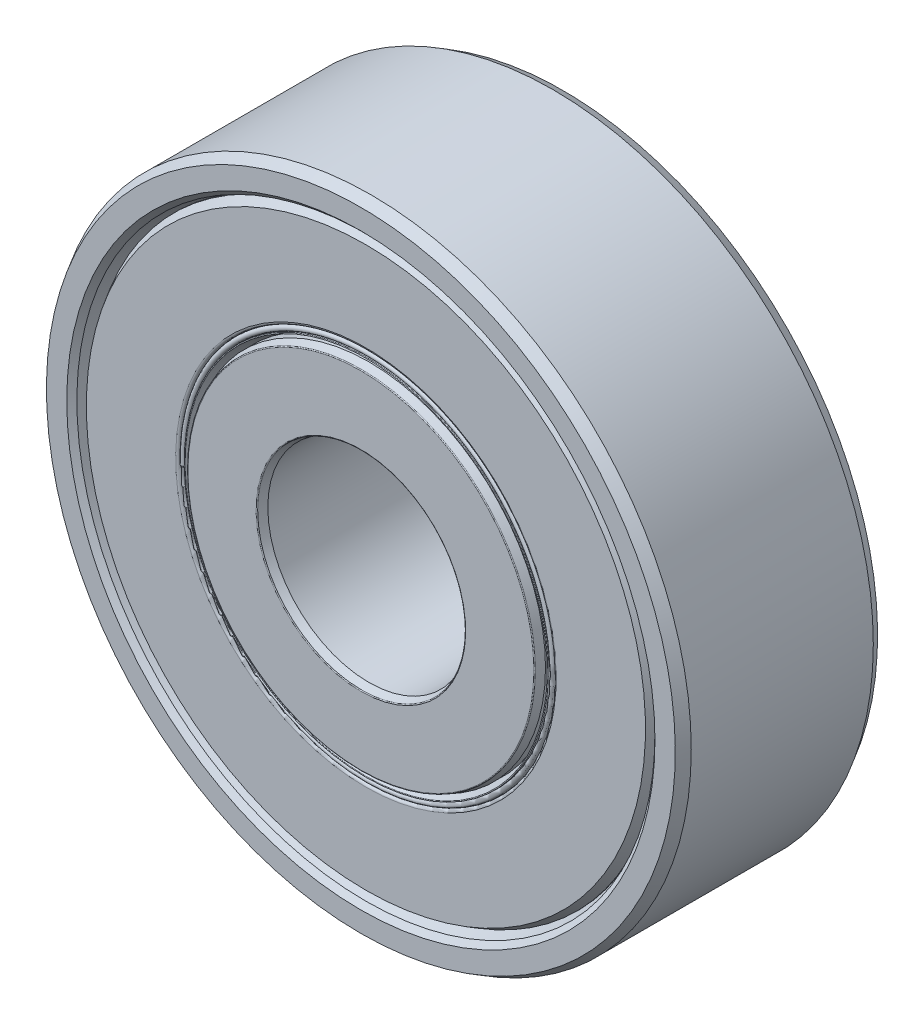
SolidWorks part; units mm, degrees
ref_plane "Front Plane" through (0, 0, 0) normal (0, 0, 1) x (1, 0, 0)
ref_plane "Top Plane" through (0, 0, 0) normal (0, 1, 0) x (1, 0, 0)
ref_plane "Right Plane" through (0, 0, 0) normal (1, 0, 0) x (0, 0, -1)
sketch "Sketch1" plane through (0, 0, 0) normal (0, 0, 1) x (1, 0, 0)
  line L0 (-9.5, 0) -> (9.5, 0) construction
  line L1 (-3, 0) -> (3, 0) construction
  circle A0 centre (0, 0) radius 3 construction
  circle A1 centre (0, 0) radius 9.5 construction
  point P3 (0, 0)
  point P6 (0, 0)
  point P7 (0, -3)
  point P11 (0, -9.5)
  point P12 (0, 3)
  point P13 (0, 9.5)
  dimension "OD" = 19
  dimension "ID" = 6
sketch "Sketch2" plane through (0, 0, 0) normal (1, 0, 0) x (0, 0, -1)
  line L0 (-3, 9.5) -> (3, 9.5) construction
  line L1 (0, 9.5) -> (0, -9.5) construction
  line L2 (2.7, 9.5) -> (-2.7, 9.5)
  line L3 (-2.7, 9.5) -> (-3, 9.3268)
  line L4 (-3, 9.3268) -> (-3, 8.7235)
  line L5 (-2.5245, 8.455) -> (-1.398, 8.455)
  line L6 (2.5245, 8.455) -> (1.398, 8.455)
  line L7 (3, 9.3268) -> (3, 8.7235)
  line L8 (2.7, 9.5) -> (3, 9.3268)
  line L9 (-1.398, 8.455) -> (-1.398, 9.5) construction
  line L10 (-1.398, 8.9775) -> (0, 8.9775) construction
  line L11 (0, 9.5) -> (0, -9.5) construction
  line L12 (-3, 0) -> (3, 0) construction
  line L13 (3, 3) -> (-3, 3) construction
  line L14 (-3, 3) -> (-3, -3) construction
  line L15 (-3, -3) -> (3, -3) construction
  line L16 (3, 9.5) -> (3, -9.5) construction
  line L20 (-2.5245, 8.455) -> (-2.85, 8.5735)
  line L21 (-2.85, 8.5735) -> (-3, 8.7235)
  line L26 (2.85, 8.5735) -> (3, 8.7235)
  line L27 (2.5245, 8.455) -> (2.85, 8.5735)
  arc A0 (-1.398, 8.455) -> (1.398, 8.455) centre (0, 6.846) cw
  circle A1 centre (0, 6.846) radius 2.1315 construction
  point P17 (0, 0)
  point P21 (0, 9.5)
  point P30 (0, -3)
  dimension "Width" = 6
  dimension "D3" = 2.796
  dimension "For Shaft Diameter" = 6
  dimension "For Housing ID" = 19
  dimension "D4" = 16.91
  dimension "D2" = 20
  dimension "D5" = 45
  dimension "D1" = 30
  dimension "D6" = 0.3
  dimension "D7" = 0.15
sketch "Sketch3" plane through (0, 0, 0) normal (1, 0, 0) x (0, 0, -1)
  line L14 (-2.5245, 8.455) -> (-2.85, 8.5735) construction
  line L15 (-2.85, 8.5735) -> (-3, 8.7235) construction
  line L16 (-3, 9.3268) -> (-3, 8.7235) construction
  line L17 (-2.7, 9.5) -> (-3, 9.3268) construction
  line L18 (2.7, 9.5) -> (-2.7, 9.5) construction
  line L19 (2.7, 9.5) -> (3, 9.3268) construction
  line L20 (3, 9.3268) -> (3, 8.7235) construction
  line L21 (2.85, 8.5735) -> (3, 8.7235) construction
  line L22 (2.5245, 8.455) -> (2.85, 8.5735) construction
  line L23 (2.5245, 8.455) -> (1.398, 8.455) construction
  line L24 (-2.5245, 8.455) -> (-1.398, 8.455) construction
  line L25 (-2.5245, 8.455) -> (-2.85, 8.5735)
  line L26 (-2.85, 8.5735) -> (-3, 8.7235)
  line L27 (-3, 9.3268) -> (-3, 8.7235)
  line L28 (-2.7, 9.5) -> (-3, 9.3268)
  line L29 (2.7, 9.5) -> (-2.7, 9.5)
  line L30 (2.7, 9.5) -> (3, 9.3268)
  line L31 (3, 9.3268) -> (3, 8.7235)
  line L32 (2.85, 8.5735) -> (3, 8.7235)
  line L33 (2.5245, 8.455) -> (2.85, 8.5735)
  line L34 (2.5245, 8.455) -> (1.398, 8.455)
  line L35 (-2.5245, 8.455) -> (-1.398, 8.455)
  arc A2 (1.398, 8.455) -> (-1.398, 8.455) centre (0, 6.846) ccw construction
  arc A3 (1.398, 8.455) -> (-1.398, 8.455) centre (0, 6.846) ccw
revolve "Revolve1" add sketch "Sketch3" angle 360 about L12
sketch "Sketch4" plane through (0, 0, 0) normal (1, 0, 0) x (0, 0, -1)
  line L0 (0, 9.5) -> (0, -9.5) construction
  line L1 (0, 9.5) -> (0, -9.5) construction
  line L2 (-2.76, 3) -> (-2.9803, 3.0802)
  line L3 (-3, 3.1084) -> (-3, 5.1287)
  line L4 (2.76, 5.237) -> (2.9803, 5.1568)
  line L5 (-2.76, 5.237) -> (-1.398, 5.237)
  line L6 (-2.76, 3) -> (2.76, 3)
  line L7 (3, 9.3268) -> (3, 8.7235) construction
  line L8 (2.76, 3) -> (2.9803, 3.0802)
  line L9 (1.398, 5.237) -> (1.398, 3) construction
  line L10 (3, 3.1084) -> (3, 5.1287)
  line L11 (2.76, 5.237) -> (1.398, 5.237)
  line L12 (-2.76, 5.237) -> (-2.9803, 5.1568)
  line L14 (1.398, 4.1185) -> (3, 4.1185) construction
  circle A0 centre (0, 6.846) radius 2.1315 construction
  arc A1 (1.398, 5.237) -> (-1.398, 5.237) centre (0, 6.846) cw
  arc A2 (2.9803, 5.1568) -> (3, 5.1287) centre (2.97, 5.1287) cw
  arc A3 (-2.9803, 5.1568) -> (-3, 5.1287) centre (-2.97, 5.1287) ccw
  arc A4 (2.9803, 3.0802) -> (3, 3.1084) centre (2.97, 3.1084) ccw
  arc A5 (-2.9803, 3.0802) -> (-3, 3.1084) centre (-2.97, 3.1084) cw
  point P14 (3, 3.0874)
  dimension "D2" = 0.03
  dimension "D1" = 20
  dimension "D3" = 0.24
revolve "Revolve2" add sketch "Sketch4" angle 360 about L12
sketch "Sketch5" plane through (0, 0, 0) normal (1, 0, 0) x (0, 0, -1)
  line L0 (-2.1315, 6.846) -> (2.1315, 6.846)
  arc A2 (-2.1315, 6.846) -> (2.1315, 6.846) centre (0, 6.846) cw
  arc A3 (1.398, 8.455) -> (-1.398, 8.455) centre (0, 6.846) ccw construction
revolve "Revolve3" add sketch "Sketch5" angle 360 about L0
pattern_circular "CirPattern1" count 6 over 360 about axis through (0, 0, 0) along (0, 0, 1) of bodies 104
sketch "Sketch6" plane through (0, 0, 0) normal (1, 0, 0) x (0, 0, -1)
  line L1 (-2.5685, 8.455) -> (-2.1315, 8.455)
  line L2 (-2.85, 8.2925) -> (-2.85, 5.6433)
  line L3 (-2.7688, 5.562) -> (-2.1315, 5.562)
  line L4 (-2.1315, 8.455) -> (-2.1315, 5.562)
  line L6 (-2.7, 9.5) -> (-3, 9.3268) construction
  line L7 (0, 9.5) -> (0, 3) construction
  line L8 (2.7688, 5.562) -> (2.1315, 5.562)
  line L9 (2.1315, 8.455) -> (2.1315, 5.562)
  line L10 (2.5685, 8.455) -> (2.1315, 8.455)
  line L11 (2.85, 8.2925) -> (2.85, 5.6433)
  line L13 (-2.76, 5.237) -> (-1.398, 5.237) construction
  line L14 (-2.85, 8.2925) -> (-2.5685, 8.455)
  line L15 (-2.5245, 8.455) -> (-1.398, 8.455) construction
  line L16 (2.85, 8.2925) -> (2.5685, 8.455)
  arc A0 (-2.85, 5.6433) -> (-2.7688, 5.562) centre (-2.7688, 5.6433) ccw
  circle A1 centre (0, 6.846) radius 2.1315 construction
  arc A2 (2.85, 5.6433) -> (2.7688, 5.562) centre (2.7688, 5.6433) cw
  point P10 (-2.85, 9.4134)
  point P26 (-2.85, 5.562)
  dimension "D3" = 0.0813
  dimension "D1" = 0.325
  dimension "D2" = 0.1625
revolve "Revolve4" add sketch "Sketch6" angle 360 about L12
sketch "Sketch7" plane through (0, 0, 0) normal (1, 0, 0) x (0, 0, -1)
  line L0 (-2.1315, 5.237) -> (-2.4736, 5.237)
  line L5 (-2.4736, 5.237) -> (-2.8401, 5.3704)
  line L6 (-2.835, 5.3995) -> (-2.7688, 5.3995)
  line L7 (0, 4.7145) -> (0, 3) construction
  line L8 (0, 9.5) -> (0, -9.5) construction
  line L9 (-2.7688, 5.562) -> (-2.1315, 5.562)
  line L12 (-2.1315, 5.562) -> (-2.1315, 5.237)
  line L13 (-2.76, 5.237) -> (-1.398, 5.237) construction
  line L14 (-2.7688, 5.562) -> (-2.1315, 5.562) construction
  line L15 (-2.1315, 8.455) -> (-2.1315, 5.562) construction
  line L16 (2.1315, 5.562) -> (2.1315, 5.237)
  line L17 (2.7688, 5.562) -> (2.1315, 5.562)
  line L18 (2.835, 5.3995) -> (2.7688, 5.3995)
  line L19 (2.4736, 5.237) -> (2.8401, 5.3704)
  line L20 (2.1315, 5.237) -> (2.4736, 5.237)
  circle A2 centre (0, 6.846) radius 2.1315 construction
  arc A5 (-2.8401, 5.3704) -> (-2.835, 5.3995) centre (-2.835, 5.3845) cw
  arc A6 (-2.7688, 5.3995) -> (-2.7688, 5.562) centre (-2.7688, 5.4808) cw
  arc A7 (2.7688, 5.3995) -> (2.7688, 5.562) centre (2.7688, 5.4808) ccw
  arc A8 (2.8401, 5.3704) -> (2.835, 5.3995) centre (2.835, 5.3845) ccw
  point P14 (-2.85, 5.4808)
  point P27 (-2.1315, 5.3995)
  point P36 (-2.85, 5.3845)
  dimension "D1" = 20
revolve "Revolve5" add sketch "Sketch7" angle 360 about L12
equation "\"D3@Sketch2\"=\"Width@Sketch2\" *.466"
equation "\"D4@Sketch2\"=\"OD@Sketch1\"*.89"
equation "\"D1@Sketch6\"=(\"OD@Sketch1\"-\"ID@Sketch1\")*.025"
equation "\"D2@Sketch6\"=\"D1@Sketch6\"*.5"
equation "\"D3@Sketch6\"=\"D1@Sketch6\"*.25"
equation "\"D3@Sketch4\"=\"Width@Sketch2\"*.04"
equation "\"D2@Sketch4\"=\"D3@Sketch4\"*.125"
equation "\"D6@Sketch2\"=\"Width@Sketch2\"*.05"
equation "\"D7@Sketch2\"=\"D6@Sketch2\"*.5"
equation "\"D2@Sketch7\"=\"D6@Sketch2\"*.05"
